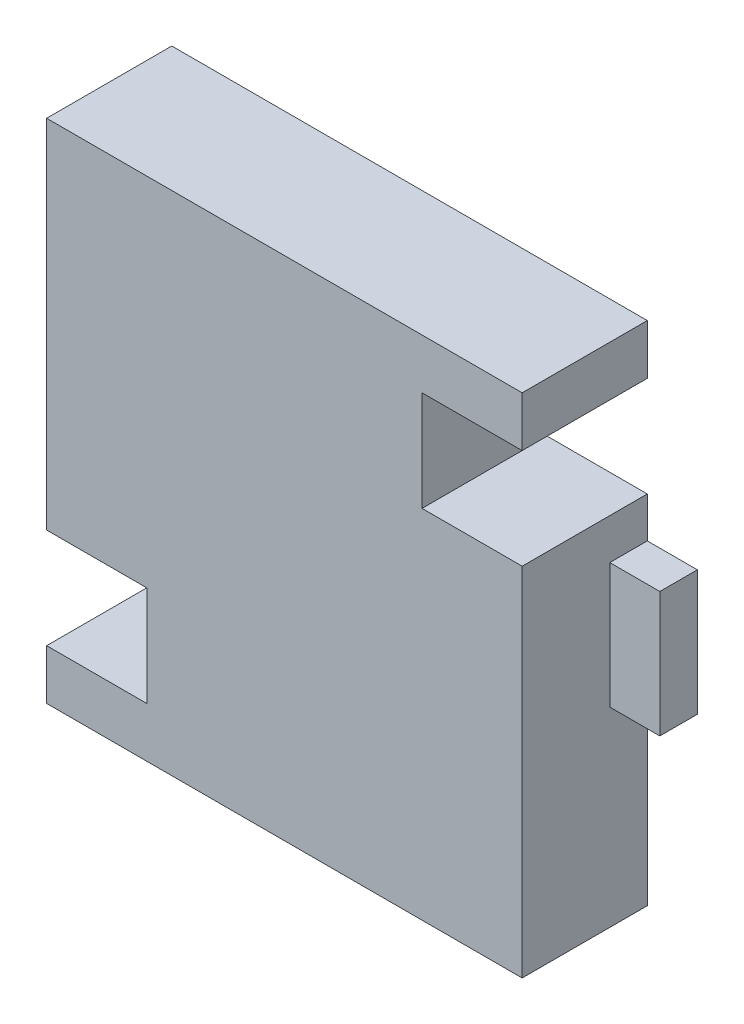
SolidWorks part; units mm, degrees
ref_plane "前视基准面" through (0, 0, 0) normal (0, 0, 1) x (1, 0, 0)
ref_plane "上视基准面" through (0, 0, 0) normal (0, 1, 0) x (1, 0, 0)
ref_plane "右视基准面" through (0, 0, 0) normal (1, 0, 0) x (0, 0, -1)
other "Configuration Table"
sketch "草图1" plane through (0, 0, 0) normal (0, 0, 1) x (1, 0, 0)
  line L0 (0, 0) -> (0, -15.25)
  line L1 (0, -15.25) -> (-4, -15.25)
  line L2 (-4, -15.25) -> (-4, -25.25)
  line L3 (-4, -25.25) -> (0, -25.25)
  line L4 (0, -25.25) -> (0, -28.5)
  line L5 (0, -28.5) -> (8, -28.5)
  line L6 (8, -28.5) -> (8, -36.5)
  line L7 (8, -36.5) -> (0, -36.5)
  line L8 (0, -36.5) -> (0, -40.5)
  line L9 (0, -40.5) -> (38, -40.5)
  line L11 (38, 0) -> (0, 0)
  line L12 (38, 0) -> (38, -4)
  line L13 (38, -4) -> (30, -4)
  line L14 (30, -4) -> (30, -12)
  line L15 (30, -12) -> (38, -12)
  line L16 (38, -12) -> (38, -15.25)
  line L17 (38, -15.25) -> (42, -15.25)
  line L18 (42, -15.25) -> (42, -25.25)
  line L19 (42, -25.25) -> (38, -25.25)
  line L20 (38, -25.25) -> (38, -40.5)
  point P11 (-4, -20.25)
  point P13 (-2, -15.25)
  point P22 (28.6004, -40.5)
  dimension "D1" = 4
  dimension "D2" = 12
  dimension "D3" = 15.25
  dimension "D4" = 10
  dimension "D5" = 3.25
  dimension "D6" = 4
  dimension "D7" = 8
  dimension "D8" = 38
extrude "凸台-拉伸1" add sketch "草图1" along normal blind 3
sketch "草图2" plane through (0, 0, 3) normal (0, 0, 1) x (1, 0, 0)
  line L0 (0, 0) -> (0, -28.5)
  line L1 (0, -28.5) -> (8, -28.5)
  line L2 (8, -28.5) -> (8, -36.5)
  line L3 (8, -36.5) -> (0, -36.5)
  line L4 (0, -36.5) -> (0, -40.5)
  line L5 (0, -40.5) -> (38, -40.5)
  line L6 (38, -40.5) -> (38, -12)
  line L7 (38, -12) -> (30, -12)
  line L8 (30, -12) -> (30, -4)
  line L9 (30, -4) -> (38, -4)
  line L10 (38, -4) -> (38, 0)
  line L11 (38, 0) -> (0, 0)
extrude "凸台-拉伸2" add sketch "草图2" along normal blind 7
